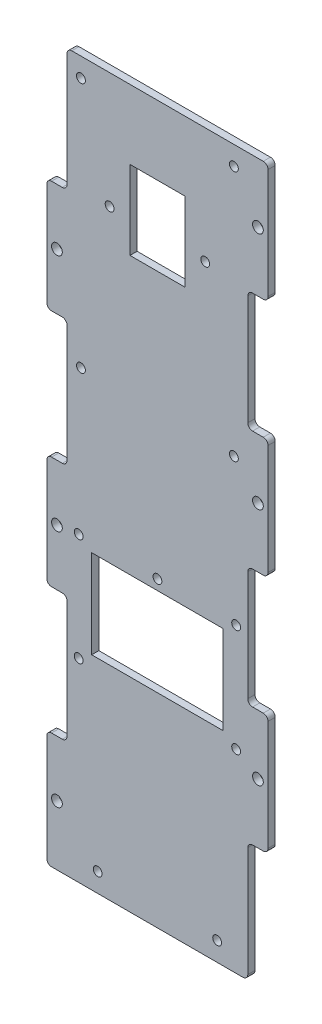
SolidWorks part; units mm, degrees
material "Acrylic (Medium-high impact)"
ref_plane "Front Plane" through (0, 0, 0) normal (0, 0, 1) x (1, 0, 0)
ref_plane "Top Plane" through (0, 0, 0) normal (0, 1, 0) x (1, 0, 0)
ref_plane "Right Plane" through (0, 0, 0) normal (1, 0, 0) x (0, 0, -1)
sketch "Sketch1" plane through (0, 0, 0) normal (0, 0, 1) x (1, 0, 0)
  line L1 (46.3, -150) -> (-46.3, -150)
  line L2 (46.3, -150) -> (46.3, 150)
  line L3 (46.3, 150) -> (-46.3, 150)
  line L4 (-46.3, -150) -> (-46.3, 150)
  line L5 (46.3, -150) -> (-46.3, 150) construction
  line L6 (46.3, 150) -> (-46.3, -150) construction
  point P0 (0, 0)
  dimension "D1" = 92.6
  dimension "D2" = 300
extrude "Boss-Extrude1" add sketch "Sketch1" along normal blind 3
sketch "Sketch2" plane through (0, 0, 0) normal (0, 0, 1) x (1, 0, 0)
  line L0 (-42.06, 150.5) -> (-42.06, -149.5) construction
  line L1 (42.06, 150) -> (42.06, -149.5) construction
  line L6 (-37.82, 98.5) -> (-46.3, 98.5)
  line L7 (-37.82, 98.5) -> (-37.82, 150)
  line L12 (-37.82, 150) -> (-46.3, 150)
  line L13 (-46.3, 98.5) -> (-46.3, 150)
  line L18 (-37.82, 98.5) -> (-46.3, 150) construction
  line L19 (-37.82, 150) -> (-46.3, 98.5) construction
  line L24 (37.82, 100) -> (46.3, 100)
  line L25 (37.82, 100) -> (37.82, 50)
  line L30 (37.82, 50) -> (46.3, 50)
  line L31 (46.3, 100) -> (46.3, 50)
  line L36 (37.82, 100) -> (46.3, 50) construction
  line L37 (37.82, 50) -> (46.3, 100) construction
  line L38 (46.3, -50) -> (37.82, -50)
  line L39 (-46.3, -150) -> (46.3, -150) construction
  line L41 (46.3, -50) -> (46.3, 0)
  line L42 (46.3, 0) -> (37.82, 0)
  line L43 (37.82, -50) -> (37.82, 0)
  line L44 (46.3, -50) -> (37.82, 0) construction
  line L45 (46.3, 0) -> (37.82, -50) construction
  line L46 (-37.82, -1.5) -> (-46.3, -1.5)
  line L47 (-37.82, -1.5) -> (-37.82, 51.5)
  line L48 (-37.82, 51.5) -> (-46.3, 51.5)
  line L49 (-46.3, -1.5) -> (-46.3, 51.5)
  line L50 (-37.82, -1.5) -> (-46.3, 51.5) construction
  line L51 (-37.82, 51.5) -> (-46.3, -1.5) construction
  line L52 (-37.82, -101.5) -> (-46.3, -101.5)
  line L53 (-37.82, -101.5) -> (-37.82, -48.5)
  line L54 (-37.82, -48.5) -> (-46.3, -48.5)
  line L55 (-46.3, -101.5) -> (-46.3, -48.5)
  line L56 (-37.82, -101.5) -> (-46.3, -48.5) construction
  line L57 (-37.82, -48.5) -> (-46.3, -101.5) construction
  line L58 (37.82, -150) -> (46.3, -150)
  line L59 (37.82, -150) -> (37.82, -100)
  line L60 (37.82, -100) -> (46.3, -100)
  line L61 (46.3, -150) -> (46.3, -100)
  line L62 (37.82, -150) -> (46.3, -100) construction
  line L63 (37.82, -100) -> (46.3, -150) construction
  line L64 (42.06, 50) -> (8.431, 50) construction
  line L65 (46.3, 150) -> (-46.3, 150) construction
  circle A6 centre (-42.06, 75) radius 2.25
  circle A7 centre (42.06, 125) radius 2.25
  circle A8 centre (42.06, 25) radius 2.25
  circle A9 centre (42.06, -75) radius 2.25
  circle A10 centre (-42.06, -25) radius 2.25
  circle A11 centre (-42.06, -125) radius 2.25
  point P8 (-42.06, 124.25)
  point P10 (-42.06, 25)
  point P19 (42.06, 75)
  point P24 (-42.06, -75)
  point P32 (42.06, -25)
  point P39 (42.06, -125)
  dimension "D1" = 4.5
  dimension "D2" = 4.5
  dimension "D12" = 4.5
  dimension "D14" = 4.5
  dimension "D20" = 4.5
  dimension "D22" = 4.5
  dimension "D3" = 25
  dimension "D4" = 84.12
  dimension "D5" = 8.48
  dimension "D6" = 51.5
  dimension "D7" = 8.48
  dimension "D8" = 50
  dimension "D9" = 50
  dimension "D10" = 8.48
  dimension "D11" = 125
  dimension "D13" = 25
  dimension "D15" = 25
  dimension "D16" = 53
  dimension "D17" = 53
  dimension "D18" = 8.48
  dimension "D19" = 75
  dimension "D21" = 50
  dimension "D23" = 8.48
  dimension "D24" = 100
  dimension "D25" = 0
  dimension "D26" = 42.06
  dimension "D27" = 0
  dimension "D28" = 0
  dimension "D29" = 75
  dimension "D30" = 75
  dimension "D31" = 25
  dimension "D32" = 175
  dimension "D33" = 75
extrude "Cut-Extrude2" cut sketch "Sketch2" along normal blind 10
fillet "Fillet1" radius 2 24 edges at (46.3, 50, 1.5) (37.82, 50, 1.5) (37.82, 100, 1.5) (46.3, 100, 1.5) (46.3, 150, 1.5) (-37.82, 150, 1.5) (-37.82, 98.5, 1.5) (-46.3, 98.5, 1.5) (-46.3, 51.5, 1.5) (-37.82, 51.5, 1.5) (-37.82, -1.5, 1.5) (-46.3, -1.5, 1.5) (-46.3, -48.5, 1.5) (-37.82, -48.5, 1.5) (-37.82, -101.5, 1.5) (-46.3, -101.5, 1.5) (-46.3, -150, 1.5) (37.82, -150, 1.5) (37.82, -100, 1.5) (46.3, -100, 1.5) (46.3, -50, 1.5) (37.82, -50, 1.5) (37.82, 0, 1.5) (46.3, 0, 1.5)
sketch "Sketch3" plane through (0, 0, 0) normal (0, 0, -1) x (-1, 0, 0)
  circle A0 centre (-25, -142) radius 1.85
  circle A1 centre (25, -142) radius 1.85
  circle A2 centre (-32, 142) radius 1.85
  circle A3 centre (32, 142) radius 1.85
  dimension "D1" = 3.7
extrude "Cut-Extrude3" cut sketch "Sketch3" against normal blind 10
sketch "Sketch4" plane through (0, 0, 0) normal (0, 0, -1) x (-1, 0, 0)
  line L0 (0, 0) -> (0, -171.2596) construction
  line L16 (27.5, -64.75) -> (-27.5, -64.75)
  line L18 (27.5, -64.75) -> (27.5, -27.75)
  line L19 (27.5, -27.75) -> (-27.5, -27.75)
  line L20 (-27.5, -64.75) -> (-27.5, -27.75)
  line L21 (27.5, -64.75) -> (-27.5, -27.75) construction
  line L22 (27.5, -27.75) -> (-27.5, -64.75) construction
  circle A5 centre (-32.95, -23.7679) radius 1.85
  circle A6 centre (0, -23.5) radius 1.85
  circle A7 centre (32.95, -23.7679) radius 1.85
  circle A8 centre (32.95, -68.7321) radius 1.85
  circle A9 centre (-32.95, -68.7321) radius 1.85
  point P3 (0, -46.25)
  dimension "D1" = 55
  dimension "D2" = 37
  dimension "D3" = 3.7
extrude "Cut-Extrude4" cut sketch "Sketch4" against normal blind 5
sketch "Sketch5" plane through (0, 0, 0) normal (0, 0, -1) x (-1, 0, 0)
  line L10 (0, 118.75) -> (0, 91.75) construction
  line L11 (5, 118.75) -> (-5, 118.75) construction
  line L12 (-5, 91.75) -> (5, 91.75) construction
  line L14 (11.5, 88) -> (-11.5, 88)
  line L15 (11.5, 88) -> (11.5, 121)
  line L16 (11.5, 121) -> (-11.5, 121)
  line L17 (-11.5, 88) -> (-11.5, 121)
  line L18 (11.5, 88) -> (-11.5, 121) construction
  line L19 (11.5, 121) -> (-11.5, 88) construction
  circle A2 centre (32, 37) radius 1.85
  circle A3 centre (-32, 37) radius 1.85
  circle A4 centre (0, 109.2) radius 4.7 construction
  circle A5 centre (-20, 101.5) radius 1.85
  circle A6 centre (20, 101.5) radius 1.85
  point P8 (0, 104.5)
  dimension "D1" = 23
  dimension "D2" = 33
  dimension "D3" = 3.7
  dimension "D4" = 3.7
extrude "Cut-Extrude5" cut sketch "Sketch5" against normal blind 5
